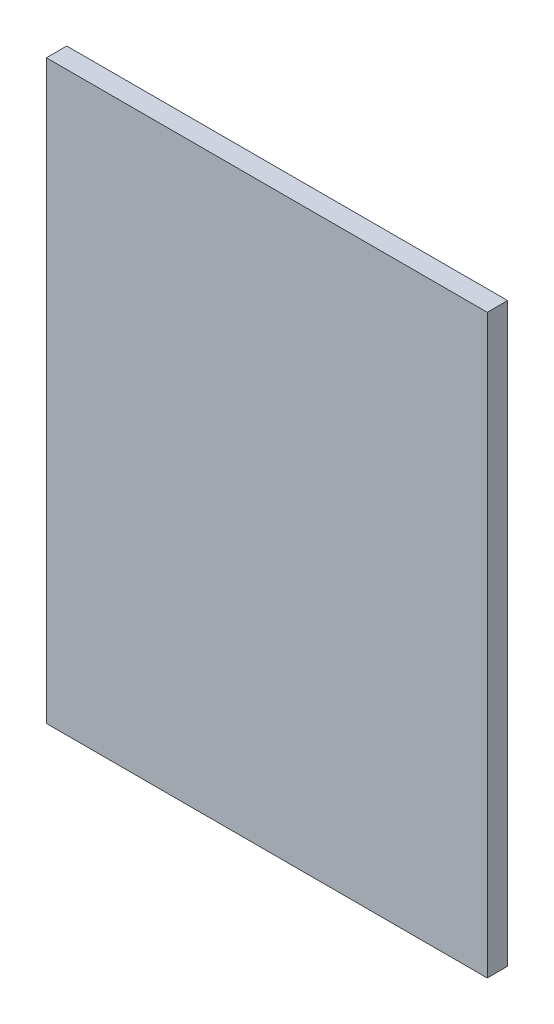
SolidWorks part; units mm, degrees
ref_plane "Front Plane" through (0, 0, 0) normal (0, 0, 1) x (1, 0, 0)
ref_plane "Top Plane" through (0, 0, 0) normal (0, 1, 0) x (1, 0, 0)
ref_plane "Right Plane" through (0, 0, 0) normal (1, 0, 0) x (0, 0, -1)
sketch "Sketch1" plane through (0, 0, 0) normal (0, 0, 1) x (1, 0, 0)
  line L1 (0, 0) -> (650, 0)
  line L2 (0, 0) -> (0, 850)
  line L3 (0, 850) -> (650, 850)
  line L4 (650, 0) -> (650, 850)
  dimension "D1" = 650
  dimension "D2" = 850
extrude "Reference_only" add sketch "Sketch1" along normal blind 30
